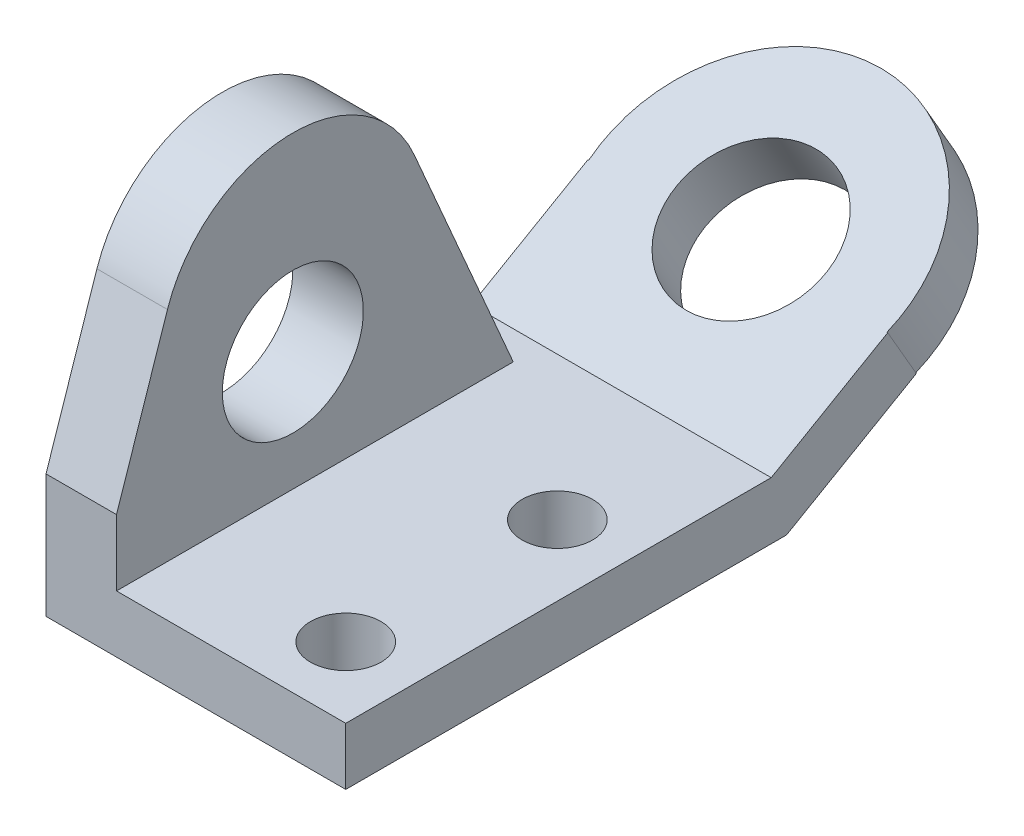
SolidWorks part; units mm, degrees
ref_plane "前视基准面" through (0, 0, 0) normal (0, 0, 1) x (1, 0, 0)
ref_plane "上视基准面" through (0, 0, 0) normal (0, 1, 0) x (1, 0, 0)
ref_plane "右视基准面" through (0, 0, 0) normal (1, 0, 0) x (0, 0, -1)
other "Configuration Table"
sketch "草图1" plane through (0, 0, 0) normal (1, 0, 0) x (0, 0, -1)
  line L0 (0, 0) -> (28.2583, 0)
  line L1 (28.2583, 0) -> (56.1949, 16.1292)
  line L2 (56.1949, 16.1292) -> (59.4449, 10.5)
  line L3 (59.4449, 10.5) -> (30, -6.5)
  line L4 (30, -6.5) -> (-20, -6.5)
  line L5 (-20, -6.5) -> (-20, 0)
  line L6 (-20, 0) -> (0, 0)
  dimension "D1" = 50
  dimension "D2" = 6.5
  dimension "D3" = 30
  dimension "D4" = 34
  dimension "D5" = 6.5
  dimension "D6" = 20
extrude "凸台-拉伸1" add sketch "草图1" against normal blind 34
sketch "草图2" plane through (0, 0, 0) normal (0, 1, 0) x (1, 0, 0)
  line L0 (0, 28.2583) -> (0, -20) construction
  line L1 (-34, -20) -> (0, -20) construction
  circle A0 centre (-8, -12) radius 4
  circle A1 centre (-8, 12) radius 4
  dimension "D3" = 8
  dimension "D4" = 8
  dimension "D1" = 8
  dimension "D2" = 8
  dimension "D5" = 24
extrude "切除-拉伸1" cut sketch "草图2" against normal up to next
sketch "草图3" plane through (-34, 0, 0) normal (-1, 0, 0) x (0, 0, 1)
  line L0 (-25, 0) -> (-13.7661, 25.9577)
  line L1 (-28.2583, 0) -> (20, 0) construction
  line L3 (20, 7.5) -> (14.2248, 24.7597)
  line L4 (20, 0) -> (20, 7.5)
  line L5 (-25, 0) -> (20, 0)
  arc A1 (14.2248, 24.7597) -> (-13.7661, 25.9577) centre (0, 20) ccw
  dimension "D2" = 30
  dimension "D3" = 20
  dimension "D4" = 25
  dimension "D5" = 7.5
extrude "凸台-拉伸2" add sketch "草图3" against normal blind 8
sketch "草图4" plane through (-34, 0, 0) normal (-1, 0, 0) x (0, 0, 1)
  circle A0 centre (0, 13.5) radius 8
  dimension "D2" = 16
  dimension "D1" = 13.5
extrude "切除-拉伸2" cut sketch "草图4" against normal up to next
sketch "草图6" plane through (0, -12.2362, -7.0646) normal (0, 0.866, 0.5) x (1, 0, 0)
  line L0 (-17, 56.7308) -> (-17, 21.0909) construction
  line L1 (-34, 56.7308) -> (0, 56.7308) construction
  line L2 (-34, 24.4724) -> (0, 24.4724) construction
  circle A0 centre (-17, 41.4724) radius 8.5
  point P6 (0, 0)
  dimension "D1" = 17
  dimension "D2" = 17
extrude "切除-拉伸3" cut sketch "草图6" against normal up to next
sketch "草图8" plane through (0, 0, 0) normal (1, 0, 0) x (0, 0, -1)
  line L0 (44.7224, 2) -> (41.4724, 7.6292)
  line L1 (30, -6.5) -> (59.4449, 10.5) construction
  line L2 (56.1949, 16.1292) -> (28.2583, 0) construction
  line L3 (41.4724, 7.6292) -> (56.1949, 16.1292)
  line L4 (56.1949, 16.1292) -> (59.4449, 10.5)
  line L5 (59.4449, 10.5) -> (44.7224, 2)
extrude "切除-拉伸4" cut sketch "草图8" against normal up to next
sketch "草图9" plane through (0, -12.2362, -7.0646) normal (0, 0.866, 0.5) x (1, 0, 0)
  circle A0 centre (-17, 41.4724) radius 17
  dimension "D1" = 34
extrude "凸台-拉伸5" add sketch "草图9" against normal blind 6.5
sketch "草图13" plane through (0, -12.2362, -7.0646) normal (0, 0.866, 0.5) x (1, 0, 0)
  circle A0 centre (-17, 41.4724) radius 8.5
  dimension "D1" = 17
extrude "切除-拉伸6" cut sketch "草图13" against normal up to next
